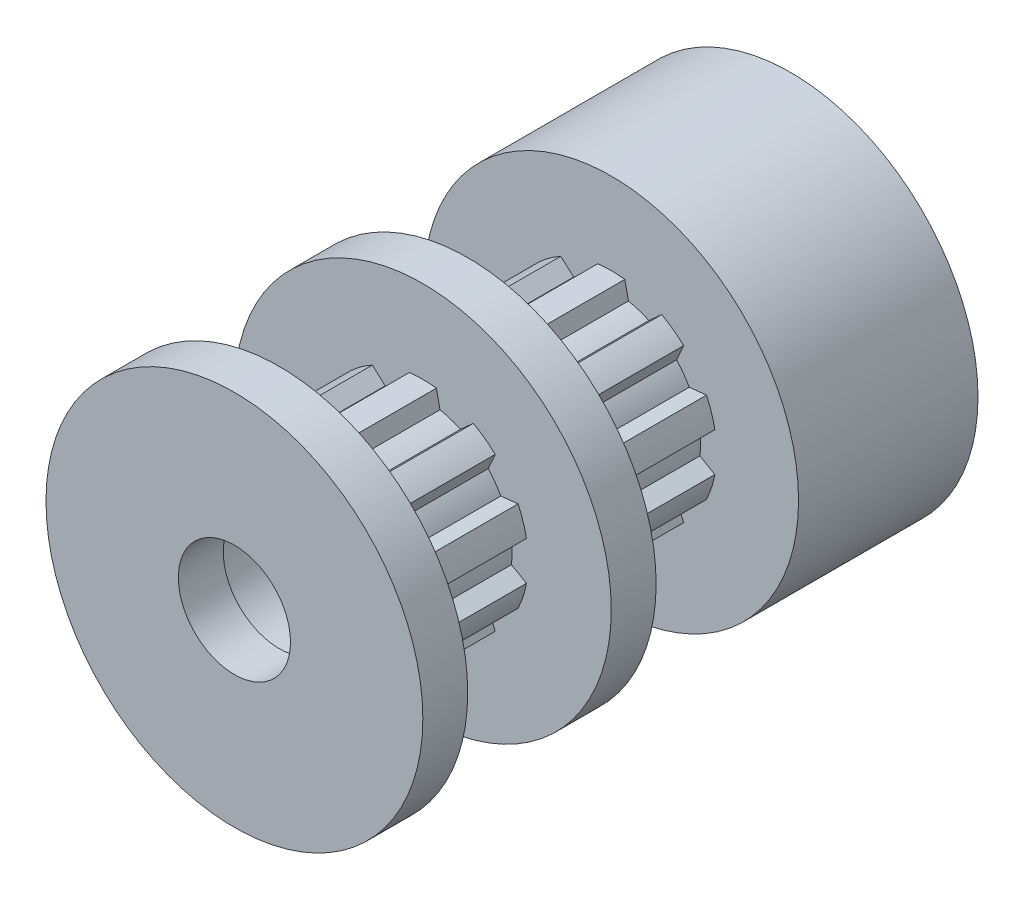
SolidWorks part; units mm, degrees
ref_plane "Front Plane" through (0, 0, 0) normal (0, 0, 1) x (1, 0, 0)
ref_plane "Top Plane" through (0, 0, 0) normal (0, 1, 0) x (1, 0, 0)
ref_plane "Right Plane" through (0, 0, 0) normal (1, 0, 0) x (0, 0, -1)
ref_plane "Plane1" through (0, 0, 7.9502) normal (0, 0, 1) x (1, 0, 0)
sketch "Sketch1" plane through (0, 0, 7.9502) normal (0, 0, 1) x (1, 0, 0)
  line L0 (-2.5089, -0.3048) -> (-2.9334, -0.5499)
  line L1 (-2.6964, -1.2793) -> (-2.2089, -1.2281)
  line L2 (-1.8505, -1.7213) -> (-2.0499, -2.1691)
  line L3 (-1.4295, -2.6199) -> (-1.0652, -2.2919)
  line L4 (-0.4854, -2.4802) -> (-0.3835, -2.9598)
  line L5 (0.3835, -2.9598) -> (0.4854, -2.4802)
  line L6 (1.0652, -2.2919) -> (1.4295, -2.6199)
  line L7 (2.0499, -2.1691) -> (1.8505, -1.7213)
  line L8 (2.2089, -1.2281) -> (2.6964, -1.2793)
  line L9 (2.9334, -0.5499) -> (2.5089, -0.3048)
  line L10 (2.5089, 0.3048) -> (2.9334, 0.5499)
  line L11 (2.6964, 1.2793) -> (2.2089, 1.2281)
  line L12 (1.8505, 1.7213) -> (2.0499, 2.1691)
  line L13 (1.4295, 2.6199) -> (1.0652, 2.2919)
  line L14 (0.4854, 2.4802) -> (0.3835, 2.9598)
  line L15 (-0.3835, 2.9598) -> (-0.4854, 2.4802)
  line L16 (-1.0652, 2.2919) -> (-1.4295, 2.6199)
  line L17 (-2.0499, 2.1691) -> (-1.8505, 1.7213)
  line L18 (-2.2089, 1.2281) -> (-2.6964, 1.2793)
  line L19 (-2.9334, 0.5499) -> (-2.5089, 0.3048)
  circle A0 centre (0, 0) radius 1.7653
  arc A1 (-2.9334, -0.5499) -> (-2.6964, -1.2793) centre (0, 0) ccw
  arc A2 (-2.2089, -1.2281) -> (-1.8505, -1.7213) centre (0, 0) ccw
  arc A3 (-2.0499, -2.1691) -> (-1.4295, -2.6199) centre (0, 0) ccw
  arc A4 (-1.0652, -2.2919) -> (-0.4854, -2.4802) centre (0, 0) ccw
  arc A5 (-0.3835, -2.9598) -> (0.3835, -2.9598) centre (0, 0) ccw
  arc A6 (0.4854, -2.4802) -> (1.0652, -2.2919) centre (0, 0) ccw
  arc A7 (1.4295, -2.6199) -> (2.0499, -2.1691) centre (0, 0) ccw
  arc A8 (1.8505, -1.7213) -> (2.2089, -1.2281) centre (0, 0) ccw
  arc A9 (2.6964, -1.2793) -> (2.9334, -0.5499) centre (0, 0) ccw
  arc A10 (2.5089, -0.3048) -> (2.5089, 0.3048) centre (0, 0) ccw
  arc A11 (2.9334, 0.5499) -> (2.6964, 1.2793) centre (0, 0) ccw
  arc A12 (2.2089, 1.2281) -> (1.8505, 1.7213) centre (0, 0) ccw
  arc A13 (2.0499, 2.1691) -> (1.4295, 2.6199) centre (0, 0) ccw
  arc A14 (1.0652, 2.2919) -> (0.4854, 2.4802) centre (0, 0) ccw
  arc A15 (0.3835, 2.9598) -> (-0.3835, 2.9598) centre (0, 0) ccw
  arc A16 (-0.4854, 2.4802) -> (-1.0652, 2.2919) centre (0, 0) ccw
  arc A17 (-1.4295, 2.6199) -> (-2.0499, 2.1691) centre (0, 0) ccw
  arc A18 (-1.8505, 1.7213) -> (-2.2089, 1.2281) centre (0, 0) ccw
  arc A19 (-2.6964, 1.2793) -> (-2.9334, 0.5499) centre (0, 0) ccw
  arc A20 (-2.5089, 0.3048) -> (-2.5089, -0.3048) centre (0, 0) ccw
extrude "Boss-Extrude1" add sketch "Sketch1" against normal blind 9.398
sketch "Sketch2" plane through (0, 0, 7.9502) normal (0, 0, 1) x (1, 0, 0)
  circle A0 centre (0, 0) radius 5.334
  circle A1 centre (0, 0) radius 1.5875
  dimension "D1" = 10.668
  dimension "D2" = 3.175
extrude "Boss-Extrude2" add sketch "Sketch2" along normal blind 1.27 contours A1 | A0
ref_plane "Plane2" through (0, 0, 3.8862) normal (0, 0, 1) x (1, 0, 0)
sketch "Sketch3" plane through (0, 0, 3.8862) normal (0, 0, 1) x (1, 0, 0)
  circle A0 centre (0, 0) radius 5.334
  circle A1 centre (0, 0) radius 1.5875
  dimension "D1" = 10.668
  dimension "D2" = 3.175
extrude "Boss-Extrude3" add sketch "Sketch3" against normal blind 1.27
sketch "Sketch4" plane through (0, 0, -1.4478) normal (0, 0, -1) x (-1, 0, 0)
  circle A0 centre (0, 0) radius 5.3023
  dimension "D1" = 10.6045
extrude "Boss-Extrude4" add sketch "Sketch4" along normal blind 5.08
ref_plane "Plane3" through (0, 5.334, 0) normal (0, 1, 0) x (1, 0, 0)
sketch "Sketch5" plane through (0, 0, 0) normal (0, 1, 0) x (1, 0, 0)
  line L0 (-5.3023, 1.4478) -> (5.3023, 1.4478) construction
  line L1 (5.3023, 1.4478) -> (5.3023, 6.5278) construction
  circle A0 centre (-0.0317, 3.9878) radius 1.016
  dimension "D1" = 2.032
  dimension "D2" = 2.54
  dimension "D3" = 5.334
extrude "Cut-Extrude1" cut sketch "Sketch5" against normal blind 7.62
sketch "Sketch7" plane through (0, 0, -6.5278) normal (0, 0, -1) x (-1, 0, 0)
  circle A0 centre (0, 0) radius 1.5875
extrude "Cut-Extrude3" cut sketch "Sketch7" against normal through all contours A0
